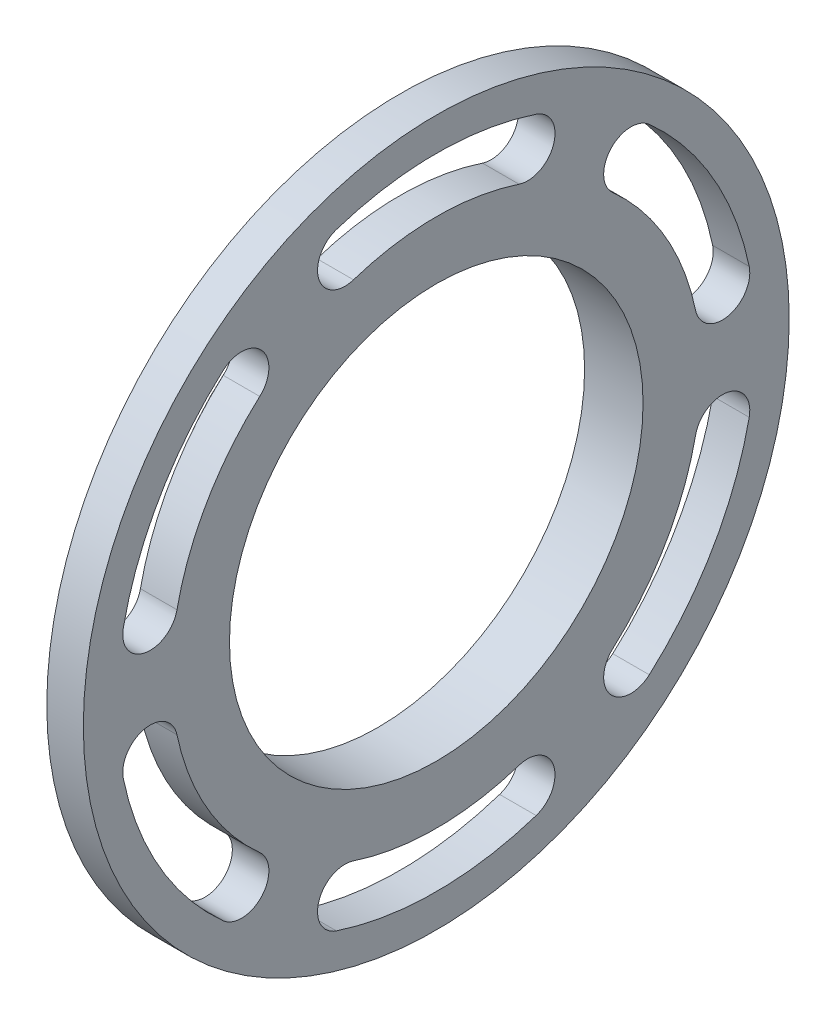
SolidWorks part; units mm, degrees
material "6061-T6 (SS)"
ref_plane "Front Plane" through (0, 0, 0) normal (0, 0, 1) x (1, 0, 0)
ref_plane "Top Plane" through (0, 0, 0) normal (0, 1, 0) x (1, 0, 0)
ref_plane "Right Plane" through (0, 0, 0) normal (1, 0, 0) x (0, 0, -1)
ref_axis "Axis1" through (88.99, 0, 0) along (-1, 0, 0)
sketch "Sketch2" plane through (0, 0, 0) normal (0, 0, 1) x (1, 0, 0)
  line L0 (0, 35.941) -> (6.35, 35.941)
  line L1 (6.35, 35.941) -> (6.35, 61.341)
  line L2 (6.35, 61.341) -> (0, 61.341)
  line L3 (0, 61.341) -> (0, 40.7035)
  line L4 (0, 40.7035) -> (-3.81, 40.7035)
  line L5 (-3.81, 40.7035) -> (-3.81, 35.941)
  line L6 (-3.81, 35.941) -> (0, 35.941)
  line L8 (88.99, 0) -> (-88.99, 0) construction
  dimension "D1" = 6.35
  dimension "D2" = 35.941
  dimension "D3" = 25.4
  dimension "D4" = 10.16
  dimension "D5" = 4.7625
revolve "Revolve1" add sketch "Sketch2" angle 360 about axis through (88.99, 0, 0) along (-1, 0, 0)
sketch "Sketch3" plane through (0, 0, 0) normal (1, 0, 0) x (0, 0, -1)
  line L0 (0, 0) -> (0, 82.0746) construction
  line L1 (0, 0) -> (-38.2732, 66.2912) construction
  line L2 (0, 0) -> (37.666, 65.2394) construction
  line L3 (0, 55.5625) -> (0, 50.8) construction
  line L4 (0, 50.8) -> (0, 46.0375) construction
  circle A0 centre (0, 0) radius 50.8 construction
  arc A1 (17.3633, 52.7798) -> (-17.3633, 52.7798) centre (0, 0) ccw
  arc A2 (14.3867, 43.7318) -> (-14.3867, 43.7318) centre (0, 0) ccw
  arc A3 (17.3633, 52.7798) -> (14.3867, 43.7318) centre (15.875, 48.2558) cw
  arc A4 (-17.3633, 52.7798) -> (-14.3867, 43.7318) centre (-15.875, 48.2558) ccw
  dimension "D2" = 101.6
  dimension "D3" = 9.525
  dimension "D4" = 31.75
  dimension "D1" = 60
extrude "Cut-Extrude1" cut sketch "Sketch3" along normal through all
pattern_circular "CirPattern1" count 6 over 360 about axis through (0, 0, 0) along (1, 0, 0) of "Cut-Extrude1"
